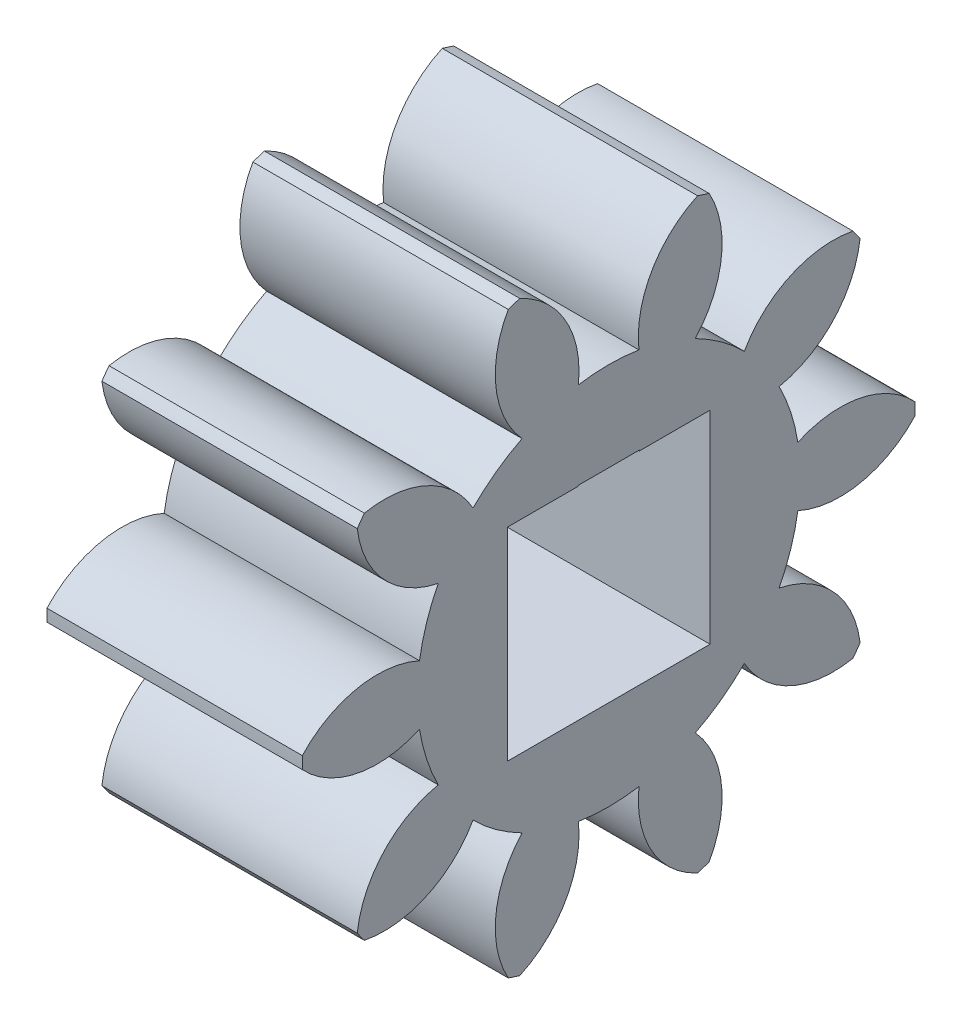
SolidWorks part; units mm, degrees
ref_plane "Plane1" through (0, 0, 0) normal (0, 0, 1) x (1, 0, 0)
ref_plane "Plane2" through (0, 0, 0) normal (0, 1, 0) x (1, 0, 0)
ref_plane "Plane3" through (0, 0, 0) normal (1, 0, 0) x (0, 0, -1)
sketch "HoldingSke" plane through (0, 0, 0) normal (0, 1, 0) x (1, 0, 0)
  line L0 (0, 0) -> (0.9848, -0.1736)
  line L1 (-15, 0) -> (100, 0) construction
  line L2 (0, 0) -> (-2.1039, 2.3779)
  line L3 (0, 0) -> (-11.863, 4.5341)
  line L4 (0, 0) -> (8.5048, 1.4996)
  line L5 (0, 0) -> (-46.8476, -17.4728)
  line L6 (0, 0) -> (-4.1448, -2.7965)
  line L7 (-2.1039, 2.3779) -> (8.6586, 51.2059)
  line L8 (-76.2, 54.61) -> (-75.7, 54.61)
  line L9 (-71.009, 38.7566) -> (-53.1078, 45.2721)
  line L10 (-76.2, 71.12) -> (104.1128, 71.12)
  line L11 (0, 0) -> (-5, 0)
  line L12 (-76.2, 101.6) -> (-76.162, 101.6)
  line L13 (24.9733, 27.94) -> (52.9518, 28.4284)
  line L14 (24.9733, 27.94) -> (24.9743, 27.94)
  line L15 (24.9733, 27.94) -> (100.4006, 29.5858)
  line L16 (-63.627, -1) -> (-12.827, -1)
  circle A0 centre (0, 0) radius 1.5
  circle A1 centre (0, 0) radius 3.749
  circle A2 centre (0, 0) radius 37.5
  circle A3 centre (0, 0) radius 1.5
  dimension "MHD" = 7.498
  dimension "Hub_dia" = 75
  dimension "Bore" = 3
  dimension "MBD" = 3
  dimension "Num_teeth" = 10
  dimension "Pitch_radius" = 180.3128
  dimension "Pitch" = 1
  dimension "Width" = 5
  dimension "Overall_len" = 50
  dimension "Show_teeth" = 10
  dimension "Thickness" = 5
  dimension "OAL" = 50.0001
  dimension "T_dim" = 0.5
  dimension "Ap" = 20
  dimension "H" = 19.05
  dimension "Backlash" = 0.038
  dimension "Addendum_fac" = 1
  dimension "Dedendum_fac" = 1.25
  dimension "Clearance_fac" = 0.25
  dimension "Dedendum_add" = 0.001
  dimension "Module" = 1
sketch "BasProSke" plane through (0, 0, 0) normal (0, 1, 0) x (1, 0, 0)
  line L0 (-10, 0) -> (60, 0) construction
  line L1 (0, 0) -> (0, 6)
  line L2 (0, 0) -> (5, 0)
  line L3 (5, 0) -> (5, 6)
  line L4 (5, 6) -> (0, 6)
  dimension "Diameter" = 12
  dimension "Thickness" = 5
revolve "Base-Revolve" add sketch "BasProSke" angle 360 about L0
sketch "TooCutSke" plane through (0, 0, 0) normal (1, 0, 0) x (0, 0, -1)
  line L1 (0, 0) -> (0, 107) construction
  line L2 (0, 0) -> (-0.8485, 4.9275) construction
  line L3 (0, 0) -> (-3.0584, 9.4126) construction
  line L4 (-0.8485, 4.9275) -> (-1.5292, 4.7063) construction
  arc A0 (0.5928, 3.7018) -> (-0.5928, 3.7018) centre (0, 0) ccw
  arc A1 (1.7758, 5.7578) -> (-1.7758, 5.7578) centre (0, 0) ccw
  circle A2 centre (0, 0) radius 5 construction
  circle A3 centre (0, 0) radius 4.6985 construction
  arc A4 (-0.5928, 3.7018) -> (-1.7758, 5.7578) centre (-2.5801, 3.9267) ccw
  arc A5 (1.7758, 5.7578) -> (0.5928, 3.7018) centre (2.5801, 3.9267) ccw
  dimension "Root_dia" = 7.498
  dimension "Overcut_dia" = 12.0508
  dimension "Pitch_dia" = 10
  dimension "Base_dia" = 9.3969
  dimension "Flank_rad" = 2
  dimension "Half_ang" = 18
  dimension "Half_CT" = 0.7157
extrude "ToothCut" cut sketch "TooCutSke" along normal through all
fillet "Breaks" [suppressed] radius 0.02
fillet "RootFillets" [suppressed] radius 0.251
pattern_circular "TeethCuts" count 10 every 36 about axis through (-10, 0, 0) along (1, 0, 0) of "ToothCut", "RootFillets", "Breaks"
sketch "HubNeaOneSke" plane through (0, 0, 0) normal (-1, 0, 0) x (0, 0, 1)
  circle A0 centre (0, 0) radius 3.749
  dimension "Diameter" = 7.498
extrude "HubNearOne" [suppressed] add sketch "HubNeaOneSke" along normal blind 45.0001
sketch "HubNeaBotSke" plane through (0, 0, 0) normal (-1, 0, 0) x (0, 0, 1)
  circle A0 centre (0, 0) radius 3.749
  dimension "Diameter" = 7.498
extrude "HubNearBoth" [suppressed] add sketch "HubNeaBotSke" along normal blind 22.5
ref_plane "FarPln" through (5, 0, 0) normal (1, 0, 0) x (0, 0, -1)
sketch "HubFarSke" plane through (5, 0, 0) normal (1, 0, 0) x (0, 0, -1)
  circle A0 centre (0, 0) radius 3.749
  dimension "Diameter" = 7.498
extrude "HubFar" [suppressed] add sketch "HubFarSke" along normal blind 22.5
sketch "BorSke" plane through (0, 0, 0) normal (1, 0, 0) x (0, 0, -1)
  circle A0 centre (0, 0) radius 1.5
  dimension "Diameter" = 3
extrude "Bore" cut sketch "BorSke" along normal mid plane 100.0001
sketch "KeySke" plane through (0, 0, 0) normal (1, 0, 0) x (0, 0, -1)
  line L0 (-0.6, 0) -> (-0.6, 2)
  line L1 (-0.6, 2) -> (0.6, 2)
  line L2 (0.6, 2) -> (0.6, 0)
  line L3 (0, 0) -> (0, 34) construction
  line L4 (-0.6, 0) -> (0.6, 0)
  dimension "Offset" = 2
  dimension "Width" = 1.2
extrude "Keyway" cut sketch "KeySke" along normal mid plane 100.0001
pattern_circular "Keyway2" [suppressed] count 2 every 90 about axis through (-10, 0, 0) along (1, 0, 0)
sketch "Sketch1" plane through (0, 0, 0) normal (-1, 0, 0) x (0, 0, 1)
  line L1 (-1.9844, 1.9844) -> (1.9844, 1.9844)
  line L2 (-1.9844, 1.9844) -> (-1.9844, -1.9844)
  line L3 (-1.9844, -1.9844) -> (1.9844, -1.9844)
  line L4 (1.9844, 1.9844) -> (1.9844, -1.9844)
  line L5 (-1.9844, 1.9844) -> (1.9844, -1.9844) construction
  line L6 (-1.9844, -1.9844) -> (1.9844, 1.9844) construction
  point P0 (0, 0)
  dimension "D1" = 3.9688
  dimension "D2" = 3.9688
extrude "Cut-Extrude1" cut sketch "Sketch1" against normal through all
equation "' \"Module@HoldingSke\" = 6.35"
equation "' \"Num_teeth@HoldingSke\" = 12"
equation "' \"Ap@HoldingSke\" =  20"
equation "' \"Width@HoldingSke\" = 0.5 * 25.4"
equation "' \"Hub_dia@HoldingSke\"= 1 * 25.4"
equation "' \"Overall_len@HoldingSke\" = 1.0 * 25.4"
equation "' \"Bore@HoldingSke\" = 0.75 * 25.4"
equation "' \"T_dim@HoldingSke\" = 0.1 * 25.4"
equation "' \"Width@KeySke\" = 0.25 * 25.4"
equation "' \"Show_teeth@HoldingSke\" = 13"
equation "' \"Backlash@HoldingSke\" = 0.009 * 25.4"
equation "' \"Addendum_fac@HoldingSke\" = 1.0"
equation "' \"Dedendum_fac@HoldingSke\" = 1.25"
equation "' \"Dedendum_add@HoldingSke\" = 0.00005 * 25.4"
equation "' \"Clearance_fac@HoldingSke\" = 0.25"
equation "\"Pitch@HoldingSke\" = 1 / \"Module@HoldingSke\""
equation "\"Overcut_dia@TooCutSke\" = (\"Num_teeth@HoldingSke\" + 2 * \"Addendum_fac@HoldingSke\") / \"Pitch@HoldingSke\" + 0.002 * 25.4"
equation "\"Pitch_dia@TooCutSke\" = \"Num_teeth@HoldingSke\" / \"Pitch@HoldingSke\""
equation "\"Base_dia@TooCutSke\" = \"Num_teeth@HoldingSke\" / \"Pitch@HoldingSke\" * cos((\"Ap@HoldingSke\"  * 3.14159265 / 180))"
equation "\"Root_dia@TooCutSke\" = (\"Num_teeth@HoldingSke\" + 2) / \"Pitch@HoldingSke\" - 2 * (\"Addendum_fac@HoldingSke\" + \"Dedendum_fac@HoldingSke\") / \"Pitch@HoldingSke\" - \"Dedendum_add@HoldingSke\" * 2"
equation "\"Half_ang@TooCutSke\" = 180 / \"Num_teeth@HoldingSke\""
equation "\"Half_CT@TooCutSke\" = \"Num_teeth@HoldingSke\" / \"Pitch@HoldingSke\" * sin((3.14159265 / 2 / \"Num_teeth@HoldingSke\")) / 2 - 7 * \"Backlash@HoldingSke\" / 4"
equation "\"Flank_rad@TooCutSke\" = \"Num_teeth@HoldingSke\" / \"Pitch@HoldingSke\" / 5"
equation "\"Radius@RootFillets\" = \"Clearance_fac@HoldingSke\" / \"Pitch@HoldingSke\" + \"Dedendum_add@HoldingSke\""
equation "\"Break_rad@Breaks\" = 0.02 / \"Pitch@HoldingSke\""
equation "\"Thickness@HoldingSke\" = \"Width@HoldingSke\""
equation "\"OAL@HoldingSke\" = \"Thickness@HoldingSke\""
equation "\"MHD@HoldingSke\" = (\"Num_teeth@HoldingSke\" + 2) / \"Pitch@HoldingSke\" - 2 * (\"Addendum_fac@HoldingSke\" + \"Dedendum_fac@HoldingSke\")  / \"Pitch@HoldingSke\" - \"Dedendum_add@HoldingSke\" * 2"
equation "\"MBD@HoldingSke\" = (\"Num_teeth@HoldingSke\" + 2) / \"Pitch@HoldingSke\" - 2 * (\"Addendum_fac@HoldingSke\" + \"Dedendum_fac@HoldingSke\")  / \"Pitch@HoldingSke\" - \"Dedendum_add@HoldingSke\" * 2 - 0.002 * 25.4"
equation "\"MHD@HoldingSke\" = ((sgn( \"MHD@HoldingSke\" - \"Hub_dia@HoldingSke\" )-1)*( \"MHD@HoldingSke\" - \"Hub_dia@HoldingSke\" ))/-2+ \"Hub_dia@HoldingSke\""
equation "\"MBD@HoldingSke\" = ((sgn( \"MBD@HoldingSke\" - \"Bore@HoldingSke\" )-1)*( \"MBD@HoldingSke\" - \"Bore@HoldingSke\" ))/-2+ \"Bore@HoldingSke\""
equation "\"OAL@HoldingSke\" = ((sgn( \"OAL@HoldingSke\" - \"Overall_len@HoldingSke\" )+1)*( \"OAL@HoldingSke\" - \"Overall_len@HoldingSke\" ))/2 + \"Overall_len@HoldingSke\" + 0.000002 * 25.4"
equation "\"Num_teeth@TeethCuts\" = int( \"Show_teeth@HoldingSke\" ) + 1"
equation "\"Num_teeth@TeethCuts\" = ((sgn( \"Num_teeth@TeethCuts\" - \"Num_teeth@HoldingSke\" )-1)*( \"Num_teeth@TeethCuts\" - \"Num_teeth@HoldingSke\" ))/-2+ \"Num_teeth@HoldingSke\""
equation "\"Num_teeth@TeethCuts\" = ((sgn( \"Num_teeth@TeethCuts\" - 2.0)+1)*( \"Num_teeth@TeethCuts\" - 2.0))/2 +2.0"
equation "\"Angle@TeethCuts\" = 360.0 / \"Num_teeth@HoldingSke\""
equation "\"Diameter@BasProSke\" = (\"Num_teeth@HoldingSke\" + 2 * \"Addendum_fac@HoldingSke\") / \"Pitch@HoldingSke\""
equation "\"Thickness@BasProSke\"  = \"Thickness@HoldingSke\""
equation "' \"Fillet_rad@BasProSke\" =  \"Thickness@HoldingSke\" * 0.05"
equation "\"MHD@HoldingSke\" = ((sgn( \"MHD@HoldingSke\" - \"Root_dia@TooCutSke\" )-1)*( \"MHD@HoldingSke\" - \"Root_dia@TooCutSke\" ))/-2+ \"Root_dia@TooCutSke\""
equation "\"Diameter@HubNeaOneSke\" = \"MHD@HoldingSke\""
equation "\"Length@HubNearOne\" = \"OAL@HoldingSke\" - \"Thickness@BasProSke\""
equation "\"Diameter@HubNeaBotSke\" = \"MHD@HoldingSke\""
equation "\"Length@HubNearBoth\" = ( \"OAL@HoldingSke\" - \"Thickness@BasProSke\" ) / 2.0"
equation "\"Thickness@FarPln\" = \"Thickness@BasProSke\""
equation "\"Diameter@HubFarSke\" = \"MHD@HoldingSke\""
equation "\"Length@HubFar\" = ( \"OAL@HoldingSke\" - \"Thickness@BasProSke\" ) / 2.0"
equation "\"Diameter@BorSke\" = \"MBD@HoldingSke\""
equation "\"D1@Bore\" = \"OAL@HoldingSke\" * 2.0"
equation "\"D1@Keyway\" = \"OAL@HoldingSke\" * 2.0"
equation "\"Offset@KeySke\" = \"T_dim@HoldingSke\" + \"MBD@HoldingSke\" / 2.0"
